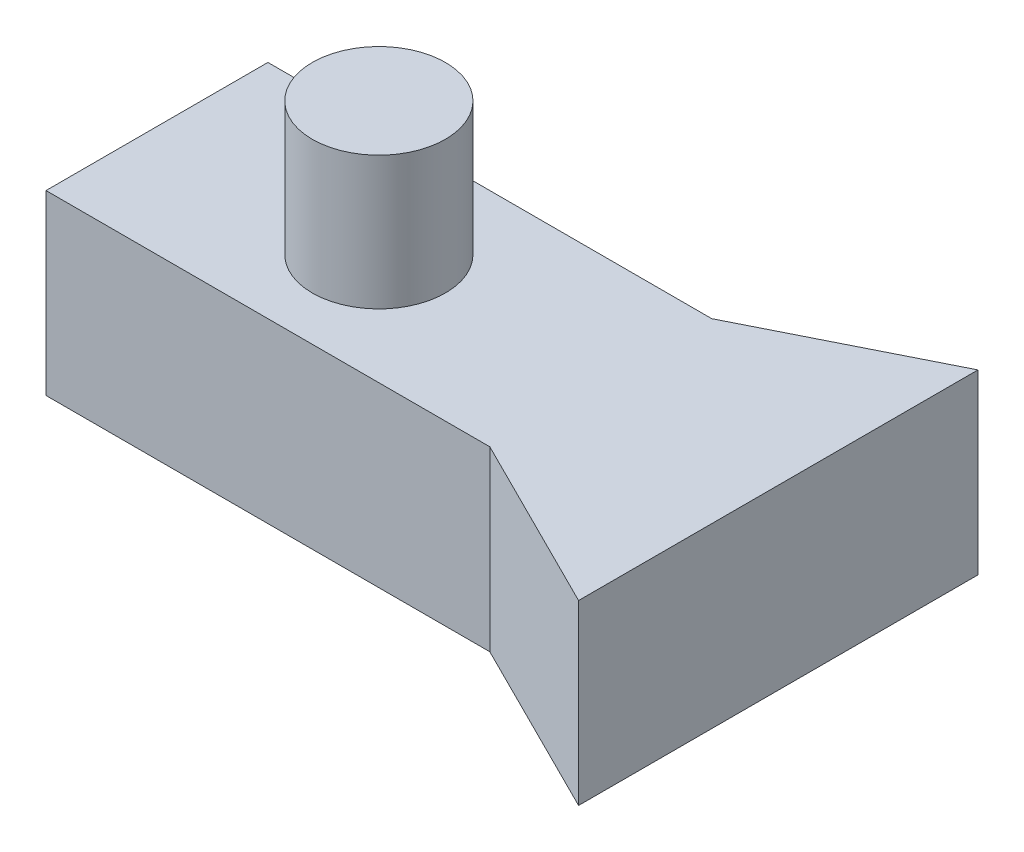
SolidWorks part; units mm, degrees
ref_plane "Front Plane" through (0, 0, 0) normal (0, 0, 1) x (1, 0, 0)
ref_plane "Top Plane" through (0, 0, 0) normal (0, 1, 0) x (1, 0, 0)
ref_plane "Right Plane" through (0, 0, 0) normal (1, 0, 0) x (0, 0, -1)
sketch "Sketch1" plane through (0, 0, 0) normal (0, 1, 0) x (1, 0, 0)
  line L0 (1000, 500) -> (1400, 700)
  line L1 (0, 0) -> (1000, 0)
  line L2 (0, 0) -> (0, 500)
  line L3 (0, 500) -> (1000, 500)
  line L4 (1000, 0) -> (1000, 500)
  line L5 (1400, 700) -> (1400, -200)
  line L6 (1400, -200) -> (1000, 0)
  line L7 (0, 0) -> (1000, 500) construction
  line L8 (0, 500) -> (1000, 0) construction
  dimension "D1" = 1000
  dimension "D2" = 500
  dimension "D3" = 400
extrude "Boss-Extrude1" add sketch "Sketch1" along normal blind 400 contours L6 L5 L0 L4 | L1 L4 L3 L2
sketch "Sketch2" plane through (0, 400, 0) normal (0, 1, 0) x (1, 0, 0)
  line L0 (0, 0) -> (1000, 500) construction
  line L1 (0, 500) -> (1000, 0) construction
  circle A0 centre (500, 250) radius 150
  point P10 (0, 0)
  dimension "D1" = 300
extrude "Boss-Extrude2" add sketch "Sketch2" along normal blind 300
